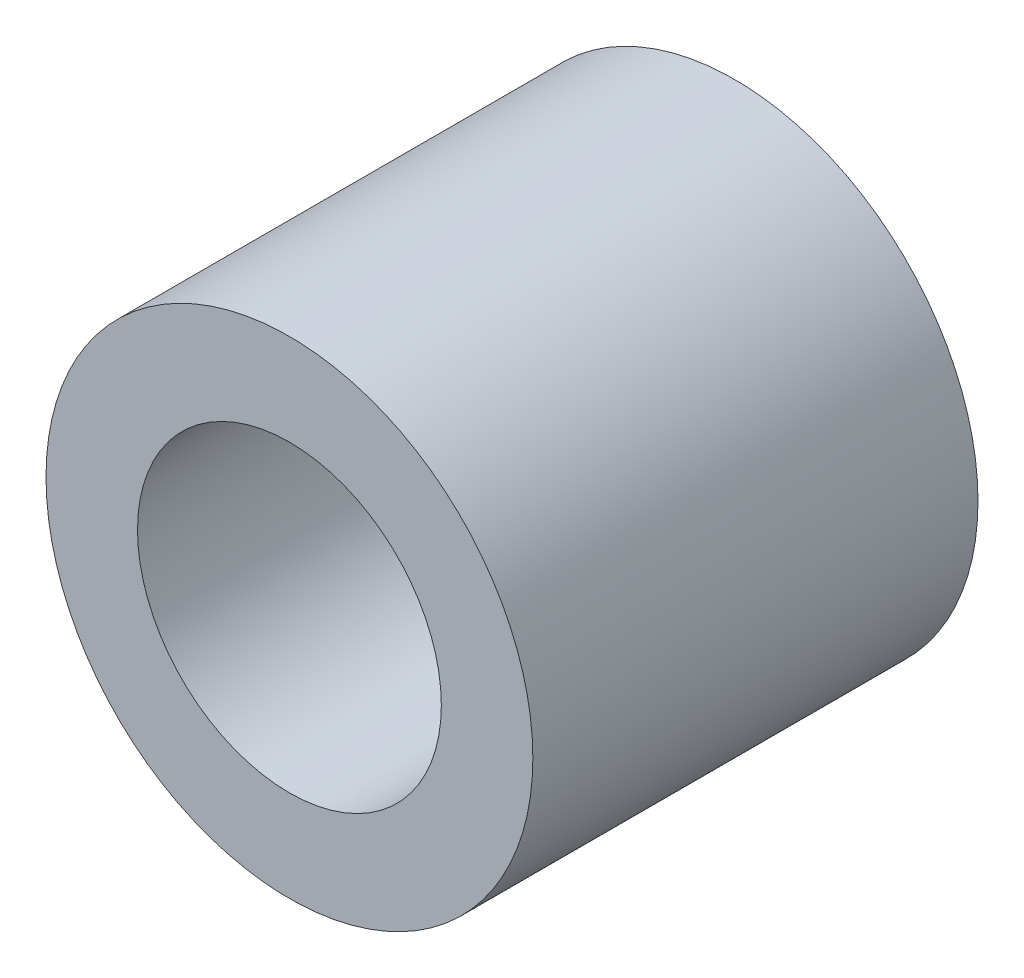
SolidWorks part; units mm, degrees
material "PVC Rigid"
ref_plane "Front" through (0, 0, 0) normal (0, 0, 1) x (1, 0, 0)
ref_plane "Top" through (0, 0, 0) normal (0, 1, 0) x (1, 0, 0)
ref_plane "Right" through (0, 0, 0) normal (1, 0, 0) x (0, 0, -1)
sketch "Sketch1" plane through (0, 0, 0) normal (0, 0, 1) x (1, 0, 0)
  circle A0 centre (0, 0) radius 6.9342
  circle A1 centre (0, 0) radius 11.1125
  dimension "D1" = 22.225
  dimension "D2" = 13.8684
extrude "Boss-Extrude1" add sketch "Sketch1" along normal blind 20.32
